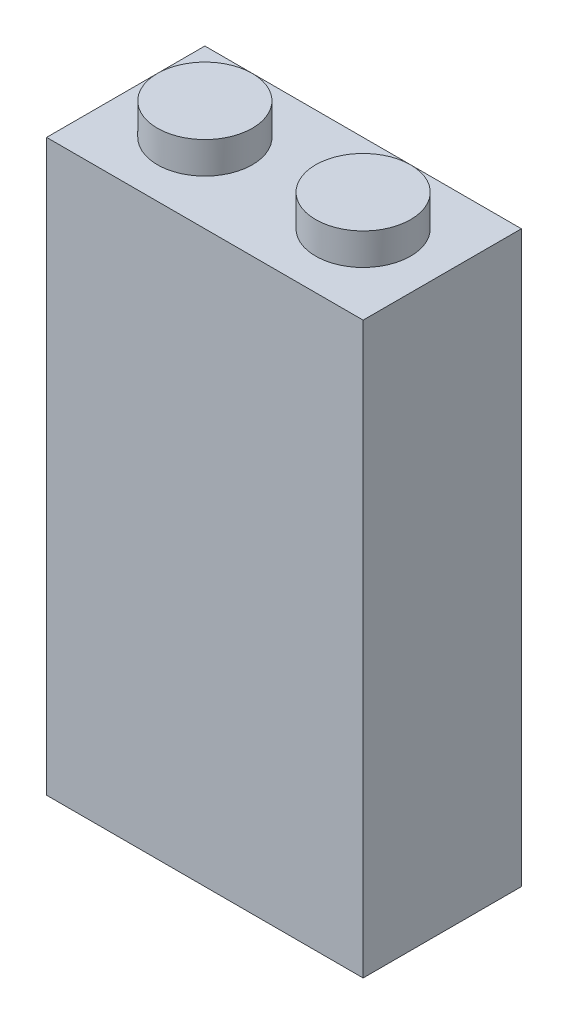
SolidWorks part; units mm, degrees
ref_plane "Front Plane" through (0, 0, 0) normal (0, 0, 1) x (1, 0, 0)
ref_plane "Top Plane" through (0, 0, 0) normal (0, 1, 0) x (1, 0, 0)
ref_plane "Right Plane" through (0, 0, 0) normal (1, 0, 0) x (0, 0, -1)
sketch "Sketch1" plane through (0, 0, 0) normal (0, 1, 0) x (1, 0, 0)
  line L1 (0, 0) -> (16, 0)
  line L2 (0, 0) -> (0, 8)
  line L3 (0, 8) -> (16, 8)
  line L4 (16, 0) -> (16, 8)
  dimension "D1" = 16
  dimension "D2" = 8
extrude "Boss-Extrude1" add sketch "Sketch1" along normal blind 28.8
sketch "Sketch2" plane through (0, 28.8, 0) normal (0, 1, 0) x (1, 0, 0)
  line L0 (8, 0) -> (8, 8) construction
  line L1 (0, 0) -> (16, 0) construction
  line L2 (16, 8) -> (0, 8) construction
  line L3 (16, 0) -> (16, 4) construction
  line L4 (16, 0) -> (16, 8) construction
  line L5 (16, 4) -> (12, 4) construction
  circle A0 centre (12, 4) radius 2.4
  dimension "D3" = 4.8
  dimension "D1" = 4
  dimension "D2" = 4
extrude "Boss-Extrude2" add sketch "Sketch2" along normal blind 1.6
pattern_linear "LPattern1" count 2 spacing 8 along (-1, 0, 0) count 4 spacing 8 along (0, 0, -1) of "Boss-Extrude2"
shell "Shell1" thickness 1.6
